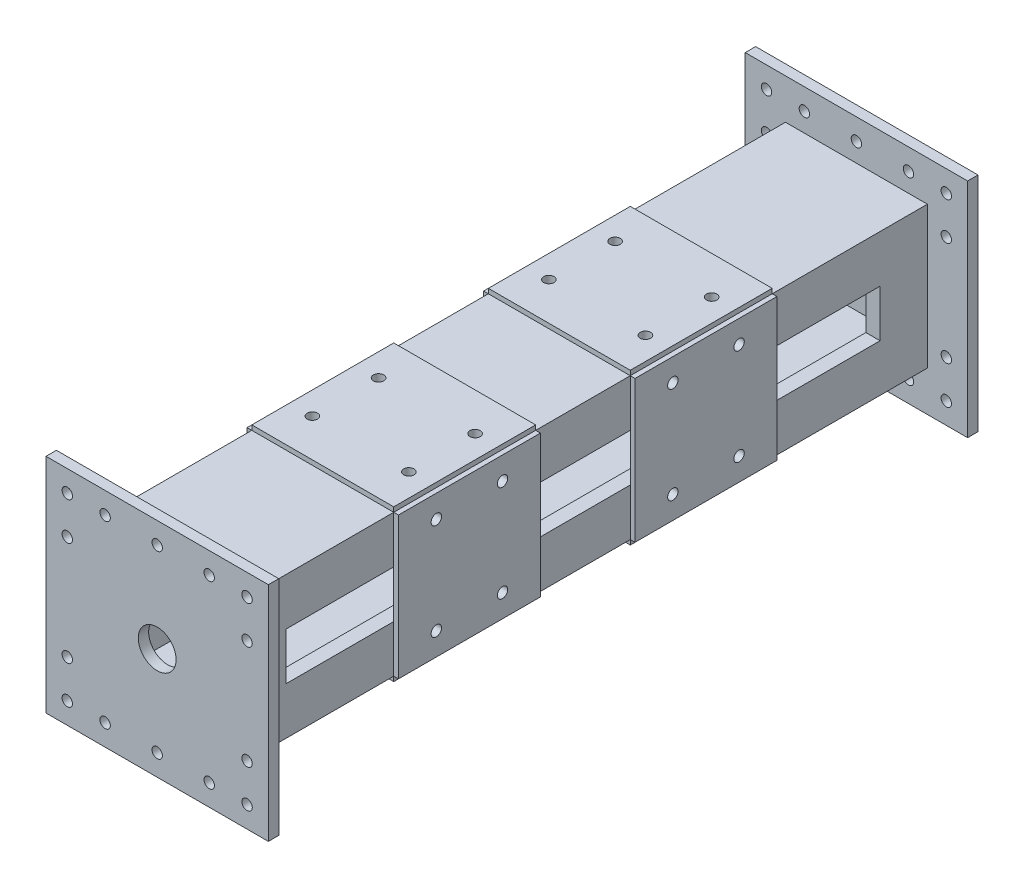
SolidWorks part; units mm, degrees
ref_plane "前视基准面" through (0, 0, 0) normal (0, 0, 1) x (1, 0, 0)
ref_plane "上视基准面" through (0, 0, 0) normal (0, 1, 0) x (1, 0, 0)
ref_plane "右视基准面" through (0, 0, 0) normal (1, 0, 0) x (0, 0, -1)
sketch "草图1" plane through (0, 0, 0) normal (0, 0, 1) x (1, 0, 0)
  line L1 (0, 0) -> (300, 0)
  line L2 (0, 0) -> (0, 300)
  line L3 (0, 300) -> (300, 300)
  line L4 (300, 0) -> (300, 300)
  dimension "D1" = 300
  dimension "D2" = 300
extrude "拉伸1" add sketch "草图1" along normal blind 1456
sketch "草图2" plane through (0, 0, 1456) normal (0, 0, 1) x (1, 0, 0)
  line L0 (300, 300) -> (0, 300) construction
  line L1 (30, 270) -> (270, 270)
  line L2 (30, 270) -> (30, 30)
  line L3 (30, 30) -> (270, 30)
  line L4 (270, 270) -> (270, 30)
  line L5 (0, 0) -> (300, 0) construction
  line L6 (0, 300) -> (0, 0) construction
  line L7 (300, 0) -> (300, 300) construction
  dimension "D1" = 30
  dimension "D2" = 30
  dimension "D3" = 30
  dimension "D4" = 30
extrude "切除-拉伸1" cut sketch "草图2" against normal through all
sketch "草图4" plane through (0, 0, 0) normal (-1, 0, 0) x (0, 0, 1)
  line L0 (0, 300) -> (0, 0) construction
  line L1 (100, 200) -> (1356, 200)
  line L2 (100, 200) -> (100, 100)
  line L3 (100, 100) -> (1356, 100)
  line L4 (1356, 200) -> (1356, 100)
  line L5 (1456, 300) -> (1456, 0) construction
  line L6 (1456, 0) -> (0, 0) construction
  line L7 (1456, 300) -> (0, 300) construction
  dimension "D1" = 100
  dimension "D2" = 100
  dimension "D3" = 100
  dimension "D4" = 100
extrude "切除-拉伸2" cut sketch "草图4" against normal through all
sketch "草图5" plane through (0, 0, 1456) normal (0, 0, 1) x (1, 0, 0)
  line L0 (0, 300) -> (0, 0) construction
  line L1 (-85, 385) -> (385, 385)
  line L2 (-85, 385) -> (-85, -85)
  line L3 (-85, -85) -> (385, -85)
  line L4 (385, 385) -> (385, -85)
  line L5 (0, 0) -> (300, 0) construction
  dimension "D1" = 470
  dimension "D2" = 470
  dimension "D3" = 85
  dimension "D4" = 85
extrude "拉伸2" add sketch "草图5" along normal blind 22
sketch "草图6" plane through (0, 0, 0) normal (0, 0, -1) x (-1, 0, 0)
  line L0 (0, 0) -> (-300, 0) construction
  line L1 (-385, 385) -> (85, 385)
  line L2 (-385, 385) -> (-385, -85)
  line L3 (-385, -85) -> (85, -85)
  line L4 (85, 385) -> (85, -85)
  line L5 (-300, 300) -> (0, 300) construction
  line L6 (-300, 0) -> (-300, 300) construction
  line L7 (0, 300) -> (0, 0) construction
  dimension "D1" = 85
  dimension "D2" = 85
  dimension "D3" = 85
  dimension "D4" = 85
extrude "拉伸3" add sketch "草图6" along normal blind 22
sketch "草图7" plane through (0, 0, 1478) normal (0, 0, 1) x (1, 0, 0)
  line L0 (-85, -85) -> (385, -85) construction
  line L1 (385, -85) -> (385, 385) construction
  circle A0 centre (-40, -40) radius 11
  circle A1 centre (40, -40) radius 11
  circle A2 centre (150, -40) radius 11
  circle A3 centre (260, -40) radius 11
  circle A4 centre (340, -40) radius 11
  circle A5 centre (-40, 340) radius 11
  circle A6 centre (40, 340) radius 11
  circle A7 centre (150, 340) radius 11
  circle A8 centre (260, 340) radius 11
  circle A9 centre (340, 340) radius 11
  circle A10 centre (-40, 40) radius 11
  circle A11 centre (-40, 260) radius 11
  circle A12 centre (340, 40) radius 11
  circle A13 centre (340, 260) radius 11
  dimension "D1" = 80
  dimension "D2" = 80
  dimension "D3" = 220
  dimension "D4" = 45
  dimension "D5" = 80
  dimension "D6" = 80
  dimension "D7" = 110
  dimension "D8" = 110
  dimension "D9" = 45
extrude "切除-拉伸3" cut sketch "草图7" against normal through all
sketch "草图8" plane through (0, 300, 0) normal (0, 1, 0) x (1, 0, 0)
  line L0 (300, -1456) -> (300, 0) construction
  line L1 (0, -328) -> (300, -328)
  line L2 (0, -328) -> (0, -628)
  line L3 (0, -628) -> (300, -628)
  line L4 (300, -328) -> (300, -628)
  line L5 (0, -828) -> (300, -828)
  line L6 (0, -828) -> (0, -1128)
  line L7 (0, -1128) -> (300, -1128)
  line L8 (300, -828) -> (300, -1128)
  line L9 (0, -1456) -> (0, 0) construction
  line L10 (300, 0) -> (0, 0) construction
  point P14 (300, -728)
  dimension "D1" = 300
  dimension "D2" = 300
  dimension "D3" = 200
  dimension "D4" = 100
extrude "拉伸4" add sketch "草图8" along normal blind 10
sketch "草图9" plane through (0, 0, 0) normal (0, -1, 0) x (1, 0, 0)
  line L0 (0, 1456) -> (0, 0) construction
  line L1 (300, 328) -> (0, 328)
  line L2 (300, 328) -> (300, 628)
  line L3 (300, 628) -> (0, 628)
  line L4 (0, 328) -> (0, 628)
  line L5 (300, 828) -> (0, 828)
  line L6 (300, 828) -> (300, 1128)
  line L7 (300, 1128) -> (0, 1128)
  line L8 (0, 828) -> (0, 1128)
  line L9 (300, 1456) -> (300, 0) construction
  line L10 (0, 0) -> (300, 0) construction
  point P14 (0, 728)
  dimension "D1" = 300
  dimension "D2" = 300
  dimension "D3" = 200
  dimension "D4" = 100
extrude "拉伸5" add sketch "草图9" along normal blind 10
sketch "草图10" plane through (300, 0, 0) normal (1, 0, 0) x (0, 0, -1)
  line L1 (-328, 300) -> (-628, 300)
  line L2 (-328, 300) -> (-328, 0)
  line L3 (-328, 0) -> (-628, 0)
  line L4 (-628, 300) -> (-628, 0)
  line L5 (-828, 300) -> (-1128, 300)
  line L6 (-828, 300) -> (-828, 0)
  line L7 (-828, 0) -> (-1128, 0)
  line L8 (-1128, 300) -> (-1128, 0)
extrude "拉伸6" add sketch "草图10" along normal blind 10
sketch "草图11" plane through (0, 0, 0) normal (-1, 0, 0) x (0, 0, 1)
  line L1 (328, 300) -> (628, 300)
  line L2 (328, 300) -> (328, 0)
  line L3 (328, 0) -> (628, 0)
  line L4 (628, 300) -> (628, 0)
  line L5 (1128, 300) -> (828, 300)
  line L6 (1128, 300) -> (1128, 0)
  line L7 (1128, 0) -> (828, 0)
  line L8 (828, 300) -> (828, 0)
extrude "拉伸7" add sketch "草图11" along normal blind 10
sketch "草图12" plane through (-10, 0, 0) normal (-1, 0, 0) x (0, 0, 1)
  line L0 (1128, 300) -> (828, 300) construction
  line L1 (1128, 0) -> (1128, 300) construction
  circle A0 centre (1048, 252) radius 11
  point P2 (978, 300)
  point P5 (1128, 150)
  dimension "D1" = 70
  dimension "D2" = 102
extrude "切除-拉伸4" cut sketch "草图12" against normal through all
pattern_linear "阵列(线性)1" count 2 spacing 140 along (0, 0, -1) count 2 spacing 204 along (0, -1, 0) of "切除-拉伸4"
pattern_linear "阵列(线性)2" count 2 spacing 500 along (0, 0, -1) of "切除-拉伸4", "阵列(线性)1"
sketch "草图13" plane through (0, -10, 0) normal (0, -1, 0) x (1, 0, 0)
  line L0 (0, 1128) -> (0, 828) construction
  line L1 (300, 1128) -> (0, 1128) construction
  circle A0 centre (48, 1048) radius 11
  point P2 (0, 978)
  point P5 (150, 1128)
  dimension "D1" = 70
  dimension "D2" = 102
extrude "切除-拉伸5" cut sketch "草图13" against normal through all
pattern_linear "阵列(线性)3" count 2 spacing 140 along (0, 0, -1) count 2 spacing 204 along (1, 0, 0) of "切除-拉伸5"
pattern_linear "阵列(线性)4" count 2 spacing 500 along (0, 0, -1) of "切除-拉伸5", "阵列(线性)3"
sketch "草图14" plane through (0, 0, 1478) normal (0, 0, 1) x (1, 0, 0)
  line L0 (385, -85) -> (385, 385) construction
  line L1 (385, 385) -> (-85, 385) construction
  circle A0 centre (150, 150) radius 40
  dimension "D1" = 235
  dimension "D2" = 235
extrude "切除-拉伸6" cut sketch "草图14" against normal through all
